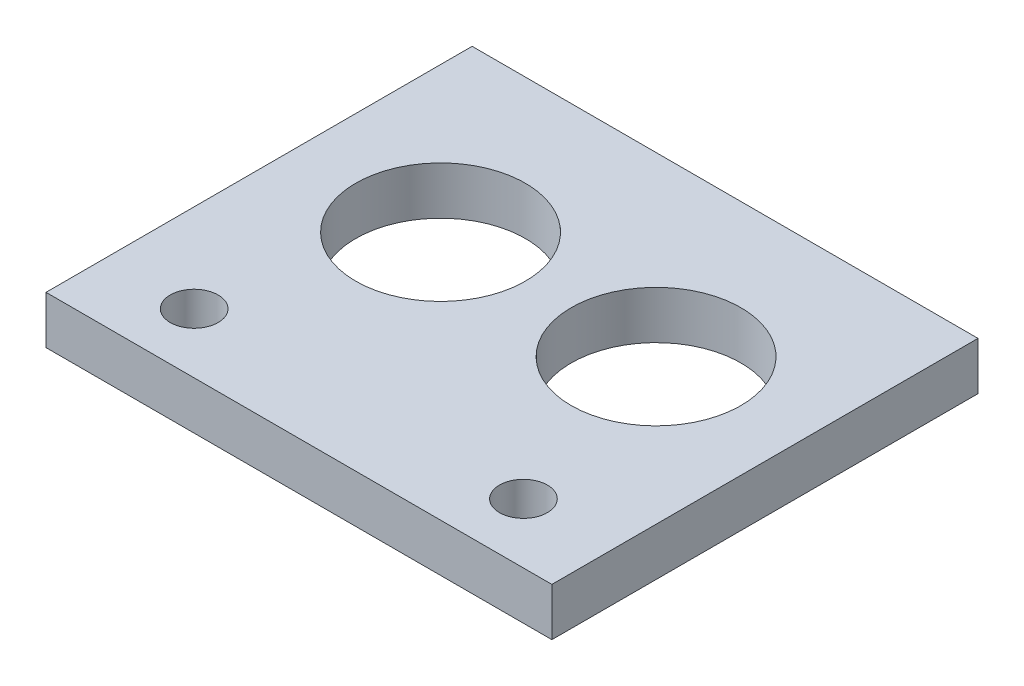
SolidWorks part; units mm, degrees
ref_plane "Front Plane" through (0, 0, 0) normal (0, 0, 1) x (1, 0, 0)
ref_plane "Top Plane" through (0, 0, 0) normal (0, 1, 0) x (1, 0, 0)
ref_plane "Right Plane" through (0, 0, 0) normal (1, 0, 0) x (0, 0, -1)
sketch "Sketch1" plane through (0, 0, 0) normal (0, 1, 0) x (1, 0, 0)
  line L0 (2.1837, -3.175) -> (19.6462, -3.175) construction
  line L1 (0, 0) -> (21.83, 0) construction
  line L2 (0, 0) -> (0, 13.75) construction
  line L3 (0, 13.75) -> (21.83, 13.75) construction
  line L4 (21.83, 0) -> (21.83, 13.75) construction
  line L5 (-2.5, 16.25) -> (24.33, 16.25)
  line L6 (-2.5, 16.25) -> (-2.5, -6.35)
  line L7 (-2.5, -6.35) -> (24.33, -6.35)
  line L8 (24.33, 16.25) -> (24.33, -6.35)
  line L9 (10.915, -6.35) -> (10.915, -3.175) construction
  line L10 (5.2, 6.875) -> (16.63, 6.875) construction
  line L11 (0, 13.75) -> (21.83, 0) construction
  circle A0 centre (5.2, 6.875) radius 4.5
  circle A1 centre (16.63, 6.875) radius 4.5
  circle A3 centre (2.1837, -3.175) radius 1.27
  circle A4 centre (19.6462, -3.175) radius 1.27
  point P15 (0, 0)
  point P20 (0, 0)
  point P21 (10.915, 6.875)
  point P22 (16.622, 6.875)
  dimension "D3" = 9
  dimension "D4" = 11.43
  dimension "D6" = 2.5
  dimension "D16" = 3.175
  dimension "D17" = 17.4625
  dimension "D18" = 2.54
  dimension "D19" = 2.54
  dimension "D1" = 21.83
  dimension "D2" = 13.75
  dimension "D7" = 2.5
  dimension "D8" = 2.5
  dimension "D9" = 6.35
extrude "Boss-Extrude1" add sketch "Sketch1" along normal blind 2.54
